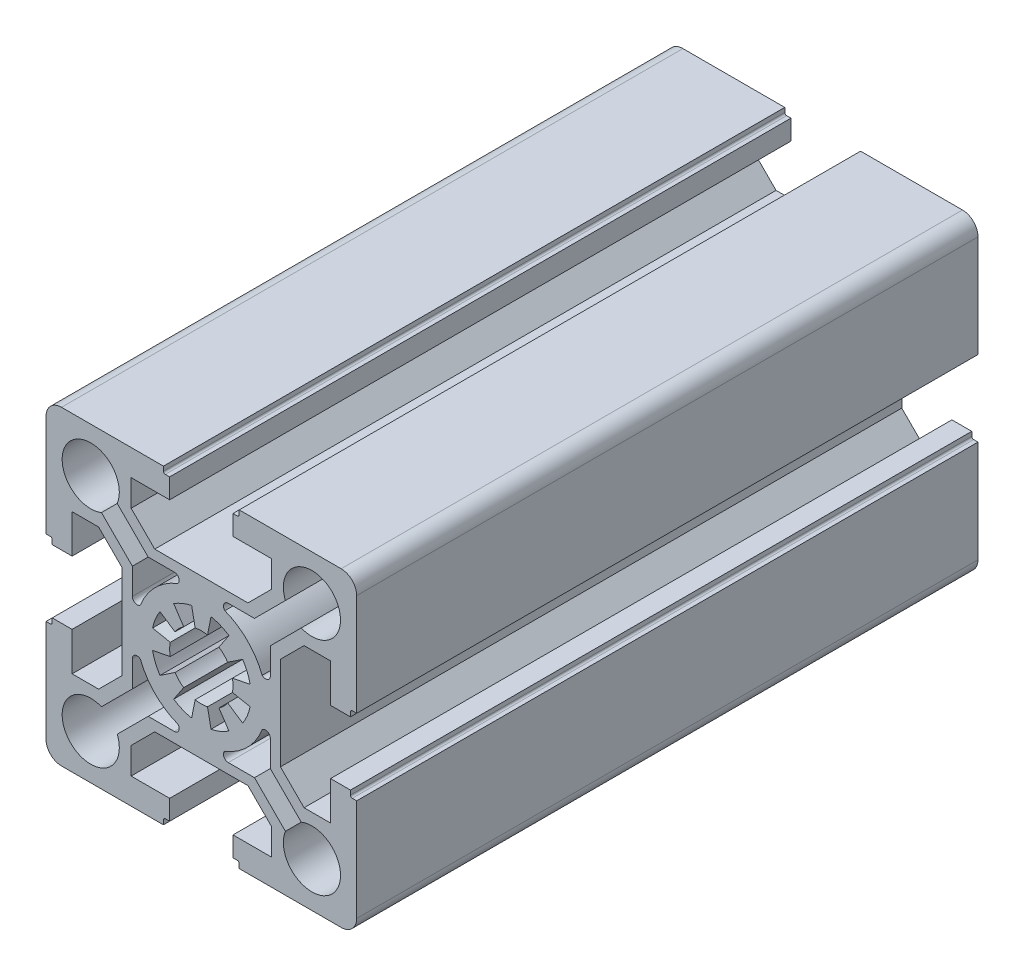
SolidWorks part; units mm, degrees
ref_plane "前视基准面" through (0, 0, 0) normal (0, 0, 1) x (1, 0, 0)
ref_plane "上视基准面" through (0, 0, 0) normal (0, 1, 0) x (1, 0, 0)
ref_plane "右视基准面" through (0, 0, 0) normal (1, 0, 0) x (0, 0, -1)
sketch "草图1" plane through (0, 0, 0) normal (0, 0, 1) x (1, 0, 0)
  line L0 (-4.766, 26.0598) -> (-21.166, 26.0598)
  line L1 (-23.666, 23.5598) -> (-23.666, 7.1598)
  line L2 (-3.766, 21.8598) -> (-9.966, 21.8598)
  line L3 (-3.766, 25.0598) -> (-4.466, 25.0598)
  line L4 (-4.766, 25.3598) -> (-4.766, 26.0598)
  line L5 (-23.666, 7.1598) -> (-22.966, 7.1598)
  line L6 (-22.666, 6.8598) -> (-22.666, 6.1598)
  line L7 (-9.966, 21.8598) -> (-9.966, 17.5924)
  line L8 (-3.766, 25.0598) -> (-3.766, 21.8598)
  line L9 (-9.766, 5.3919) -> (-9.766, 9.6142)
  line L10 (-3.1105, -5.5919) -> (-1.4994, -3.1807)
  line L11 (-0.2267, -6.7865) -> (0.3391, -3.9422)
  line L12 (2.8947, -6.7865) -> (2.329, -3.9422)
  line L13 (5.7786, -5.5919) -> (4.1674, -3.1807)
  line L14 (7.9858, -3.3847) -> (5.5745, -1.7736)
  line L15 (9.1803, -0.5009) -> (6.336, 0.0649)
  line L16 (9.1803, 2.6205) -> (6.336, 2.0548)
  line L17 (7.9858, 5.5044) -> (5.5745, 3.8932)
  line L18 (5.7786, 7.7116) -> (4.1674, 5.3003)
  line L19 (2.8947, 8.9061) -> (2.329, 6.0618)
  line L20 (-0.2267, 8.9061) -> (0.3391, 6.0618)
  line L21 (-3.1105, 7.7116) -> (-1.4994, 5.3003)
  line L22 (-5.3177, 5.5044) -> (-2.9065, 3.8932)
  line L23 (-6.5123, 2.6205) -> (-3.668, 2.0548)
  line L24 (-6.5123, -0.5009) -> (-3.668, 0.0649)
  line L25 (-5.3177, -3.3847) -> (-2.9065, -1.7736)
  line L26 (-14.7454, 14.5937) -> (-9.766, 9.6142)
  line L27 (-9.966, 17.5924) -> (-6.166, 13.7924)
  line L28 (-12.1999, 17.1393) -> (-7.2204, 12.1598)
  line L29 (-2.9981, 12.1598) -> (-7.2204, 12.1598)
  line L30 (1.334, 13.7924) -> (-6.166, 13.7924)
  line L31 (7.434, 26.0598) -> (23.834, 26.0598)
  line L32 (26.334, 23.5598) -> (26.334, 7.1598)
  line L33 (6.434, 21.8598) -> (12.634, 21.8598)
  line L34 (6.434, 25.0598) -> (7.134, 25.0598)
  line L35 (7.434, 25.3598) -> (7.434, 26.0598)
  line L36 (26.334, 7.1598) -> (25.634, 7.1598)
  line L37 (25.334, 6.8598) -> (25.334, 6.1598)
  line L38 (12.634, 21.8598) -> (12.634, 17.5924)
  line L39 (6.434, 25.0598) -> (6.434, 21.8598)
  line L40 (12.634, 17.5924) -> (8.834, 13.7924)
  line L41 (1.334, 13.7924) -> (8.834, 13.7924)
  line L42 (-4.766, -23.9402) -> (-21.166, -23.9402)
  line L43 (-23.666, -21.4402) -> (-23.666, -5.0402)
  line L44 (-3.766, -22.9402) -> (-4.466, -22.9402)
  line L45 (-4.766, -23.2402) -> (-4.766, -23.9402)
  line L46 (-23.666, -5.0402) -> (-22.966, -5.0402)
  line L47 (-22.666, -4.7402) -> (-22.666, -4.0402)
  line L48 (7.434, -23.9402) -> (23.834, -23.9402)
  line L49 (26.334, -21.4402) -> (26.334, -5.0402)
  line L50 (6.434, -22.9402) -> (7.134, -22.9402)
  line L51 (7.434, -23.2402) -> (7.434, -23.9402)
  line L52 (26.334, -5.0402) -> (25.634, -5.0402)
  line L53 (25.334, -4.7402) -> (25.334, -4.0402)
  line L54 (-3.766, -19.7402) -> (-9.966, -19.7402)
  line L55 (-9.966, -19.7402) -> (-9.966, -15.4728)
  line L56 (-3.766, -22.9402) -> (-3.766, -19.7402)
  line L57 (-9.966, -15.4728) -> (-6.166, -11.6728)
  line L58 (1.334, -11.6728) -> (-6.166, -11.6728)
  line L59 (6.434, -19.7402) -> (12.634, -19.7402)
  line L60 (12.634, -19.7402) -> (12.634, -15.4728)
  line L61 (6.434, -22.9402) -> (6.434, -19.7402)
  line L62 (12.634, -15.4728) -> (8.834, -11.6728)
  line L63 (1.334, -11.6728) -> (8.834, -11.6728)
  line L64 (-19.466, 6.1598) -> (-19.466, 12.3598)
  line L65 (-19.466, 12.3598) -> (-15.1986, 12.3598)
  line L66 (-22.666, 6.1598) -> (-19.466, 6.1598)
  line L67 (-15.1986, 12.3598) -> (-11.3986, 8.5598)
  line L68 (-11.3986, 1.0598) -> (-11.3986, 8.5598)
  line L69 (-19.466, -4.0402) -> (-19.466, -10.2402)
  line L70 (-19.466, -10.2402) -> (-15.1986, -10.2402)
  line L71 (-22.666, -4.0402) -> (-19.466, -4.0402)
  line L72 (-15.1986, -10.2402) -> (-11.3986, -6.4402)
  line L73 (-11.3986, 1.0598) -> (-11.3986, -6.4402)
  line L74 (22.134, 6.1598) -> (22.134, 12.3598)
  line L75 (22.134, 12.3598) -> (17.8666, 12.3598)
  line L76 (25.334, 6.1598) -> (22.134, 6.1598)
  line L77 (17.8666, 12.3598) -> (14.0666, 8.5598)
  line L78 (14.0666, 1.0598) -> (14.0666, 8.5598)
  line L79 (22.134, -4.0402) -> (22.134, -10.2402)
  line L80 (22.134, -10.2402) -> (17.8666, -10.2402)
  line L81 (25.334, -4.0402) -> (22.134, -4.0402)
  line L82 (17.8666, -10.2402) -> (14.0666, -6.4402)
  line L83 (14.0666, 1.0598) -> (14.0666, -6.4402)
  line L84 (12.434, 5.3919) -> (12.434, 9.6142)
  line L85 (17.4135, 14.5937) -> (12.434, 9.6142)
  line L86 (14.8679, 17.1393) -> (9.8884, 12.1598)
  line L87 (5.6661, 12.1598) -> (9.8884, 12.1598)
  line L88 (-9.766, -3.2723) -> (-9.766, -7.4946)
  line L89 (-14.7454, -12.4741) -> (-9.766, -7.4946)
  line L90 (-12.1999, -15.0196) -> (-7.2204, -10.0402)
  line L91 (-2.9981, -10.0402) -> (-7.2204, -10.0402)
  line L92 (12.434, -3.2723) -> (12.434, -7.4946)
  line L93 (17.4135, -12.4741) -> (12.434, -7.4946)
  line L94 (14.8679, -15.0196) -> (9.8884, -10.0402)
  line L95 (5.6661, -10.0402) -> (9.8884, -10.0402)
  arc A0 (-21.166, 26.0598) -> (-23.666, 23.5598) centre (-21.166, 23.5598) ccw
  arc A1 (-4.766, 25.3598) -> (-4.466, 25.0598) centre (-4.466, 25.3598) ccw
  arc A2 (-22.666, 6.8598) -> (-22.966, 7.1598) centre (-22.966, 6.8598) ccw
  arc A3 (0.3391, -3.9422) -> (2.329, -3.9422) centre (1.334, 1.0598) ccw
  arc A4 (4.1674, -3.1807) -> (5.5745, -1.7736) centre (1.334, 1.0598) ccw
  arc A5 (6.336, 0.0649) -> (6.336, 2.0548) centre (1.334, 1.0598) ccw
  arc A6 (5.5745, 3.8932) -> (4.1674, 5.3003) centre (1.334, 1.0598) ccw
  arc A7 (2.329, 6.0618) -> (0.3391, 6.0618) centre (1.334, 1.0598) ccw
  arc A8 (-1.4994, 5.3003) -> (-2.9065, 3.8932) centre (1.334, 1.0598) ccw
  arc A9 (-3.668, 2.0548) -> (-3.668, 0.0649) centre (1.334, 1.0598) ccw
  arc A10 (-2.9065, -1.7736) -> (-1.4994, -3.1807) centre (1.334, 1.0598) ccw
  arc A11 (-3.1105, -5.5919) -> (-0.2267, -6.7865) centre (1.334, 1.0598) ccw
  arc A12 (2.8947, -6.7865) -> (5.7786, -5.5919) centre (1.334, 1.0598) ccw
  arc A13 (7.9858, -3.3847) -> (9.1803, -0.5009) centre (1.334, 1.0598) ccw
  arc A14 (9.1803, 2.6205) -> (7.9858, 5.5044) centre (1.334, 1.0598) ccw
  arc A15 (5.7786, 7.7116) -> (2.8947, 8.9061) centre (1.334, 1.0598) ccw
  arc A16 (-0.2267, 8.9061) -> (-3.1105, 7.7116) centre (1.334, 1.0598) ccw
  arc A17 (-5.3177, 5.5044) -> (-6.5123, 2.6205) centre (1.334, 1.0598) ccw
  arc A18 (-6.5123, -0.5009) -> (-5.3177, -3.3847) centre (1.334, 1.0598) ccw
  arc A19 (-2.4506, 10.854) -> (-8.4602, 4.8444) centre (1.334, 1.0598) ccw
  arc A20 (-9.766, 5.3919) -> (-8.4602, 4.8444) centre (-8.9983, 5.3919) ccw
  arc A21 (-2.4506, 10.854) -> (-2.9981, 12.1598) centre (-2.9981, 11.3922) ccw
  arc A22 (26.334, 23.5598) -> (23.834, 26.0598) centre (23.834, 23.5598) ccw
  arc A23 (7.134, 25.0598) -> (7.434, 25.3598) centre (7.134, 25.3598) ccw
  arc A24 (25.634, 7.1598) -> (25.334, 6.8598) centre (25.634, 6.8598) ccw
  arc A25 (-23.666, -21.4402) -> (-21.166, -23.9402) centre (-21.166, -21.4402) ccw
  arc A26 (-4.466, -22.9402) -> (-4.766, -23.2402) centre (-4.466, -23.2402) ccw
  arc A27 (-22.966, -5.0402) -> (-22.666, -4.7402) centre (-22.966, -4.7402) ccw
  arc A28 (23.834, -23.9402) -> (26.334, -21.4402) centre (23.834, -21.4402) ccw
  arc A29 (7.434, -23.2402) -> (7.134, -22.9402) centre (7.134, -23.2402) ccw
  arc A30 (25.334, -4.7402) -> (25.634, -5.0402) centre (25.634, -4.7402) ccw
  arc A31 (-12.1999, 17.1393) -> (-14.7454, 14.5937) centre (-16.466, 18.8598) ccw
  arc A32 (11.1282, 4.8444) -> (5.1186, 10.854) centre (1.334, 1.0598) ccw
  arc A33 (11.1282, 4.8444) -> (12.434, 5.3919) centre (11.6664, 5.3919) ccw
  arc A34 (5.6661, 12.1598) -> (5.1186, 10.854) centre (5.6661, 11.3922) ccw
  arc A35 (17.4135, 14.5937) -> (14.8679, 17.1393) centre (19.134, 18.8598) ccw
  arc A36 (-8.4602, -2.7248) -> (-2.4506, -8.7344) centre (1.334, 1.0598) ccw
  arc A37 (-8.4602, -2.7248) -> (-9.766, -3.2723) centre (-8.9983, -3.2723) ccw
  arc A38 (-2.9981, -10.0402) -> (-2.4506, -8.7344) centre (-2.9981, -9.2725) ccw
  arc A39 (-14.7454, -12.4741) -> (-12.1999, -15.0196) centre (-16.466, -16.7402) ccw
  arc A40 (5.1186, -8.7344) -> (11.1282, -2.7248) centre (1.334, 1.0598) ccw
  arc A41 (12.434, -3.2723) -> (11.1282, -2.7248) centre (11.6664, -3.2723) ccw
  arc A42 (5.1186, -8.7344) -> (5.6661, -10.0402) centre (5.6661, -9.2725) ccw
  arc A43 (14.8679, -15.0196) -> (17.4135, -12.4741) centre (19.134, -16.7402) ccw
extrude "凸台-拉伸1" add sketch "草图1" along normal blind 100
